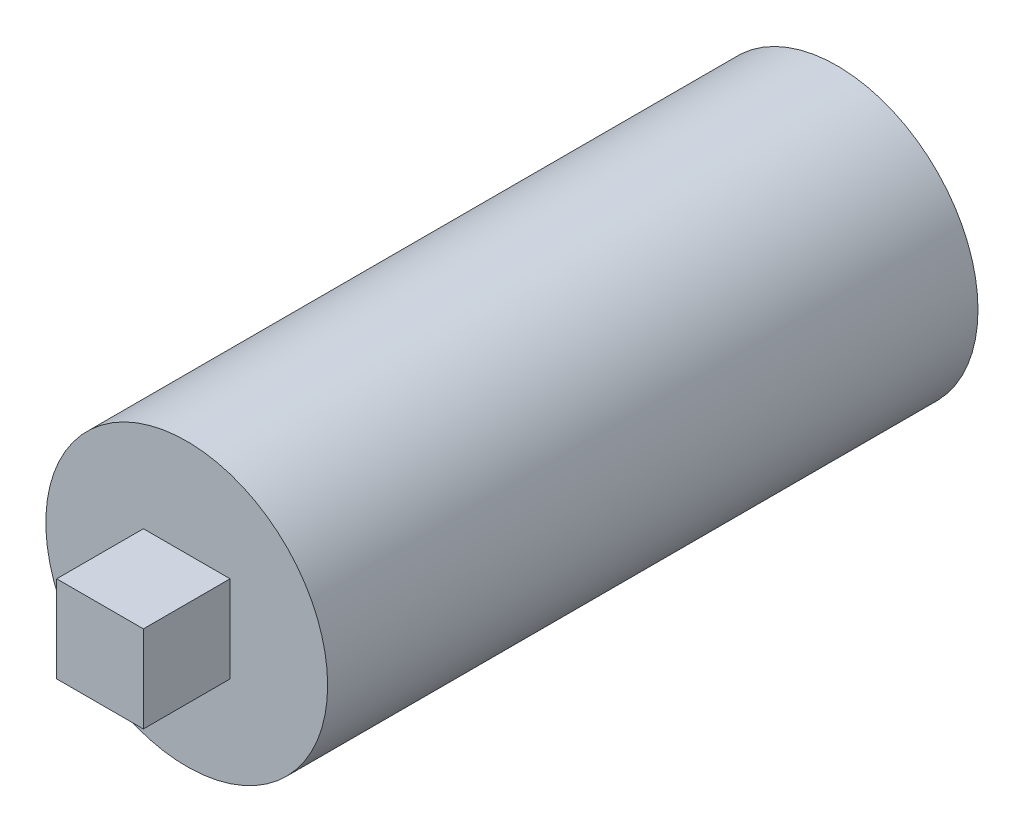
SolidWorks part; units mm, degrees
ref_plane "Ön Düzlem" through (0, 0, 0) normal (0, 0, 1) x (1, 0, 0)
ref_plane "Üst Düzlem" through (0, 0, 0) normal (0, 1, 0) x (1, 0, 0)
ref_plane "Sağ Düzlem" through (0, 0, 0) normal (1, 0, 0) x (0, 0, -1)
sketch "Çizim2" plane through (0, 0, 0) normal (0, 0, 1) x (1, 0, 0)
  circle A0 centre (0, 0) radius 32.5
  dimension "D1" = 65
extrude "Yükseklik-Ekstrüzyon1" add sketch "Çizim2" along normal blind 150
sketch "Çizim3" plane through (0, 0, 150) normal (0, 0, 1) x (1, 0, 0)
  line L0 (0, 32.5) -> (0, 0)
  line L1 (0, 10) -> (0, -0.3275)
  line L2 (-10, 10) -> (10, 10)
  line L3 (-10, 10) -> (-10, -10)
  line L4 (-10, -10) -> (10, -10)
  line L5 (10, 10) -> (10, -10)
  circle A0 centre (0, 0) radius 32.5 construction
  dimension "D1" = 32.5
  dimension "D2" = 20
  dimension "D3" = 20
extrude "Yükseklik-Ekstrüzyon2" add sketch "Çizim3" along normal blind 20
sketch "Çizim5" plane through (0, 0, 0) normal (0, 0, -1) x (-1, 0, 0)
  line L2 (-10, 10.2327) -> (10, 10.2327)
  line L3 (-10, 10.2327) -> (-10, -9.7673)
  line L4 (-10, -9.7673) -> (10, -9.7673)
  line L5 (10, 10.2327) -> (10, -9.7673)
  dimension "D1" = 20
  dimension "D2" = 20
extrude "Kes-Ekstrüzyon2" cut sketch "Çizim5" against normal blind 20 contours L3 L2 L5 L4
sketch "Çizim6" plane through (0, 0, 0) normal (0, 0, -1) x (-1, 0, 0)
  line L2 (-10.05, 10.2827) -> (-10.05, -9.8173)
  line L3 (-10.05, -9.8173) -> (10.05, -9.8173)
  line L4 (10.05, -9.8173) -> (10.05, 10.2827)
  line L5 (10.05, 10.2827) -> (-10.05, 10.2827)
extrude "Kes-Ekstrüzyon3" cut sketch "Çizim6" against normal blind 20 contours L3 L4 L5 L2
